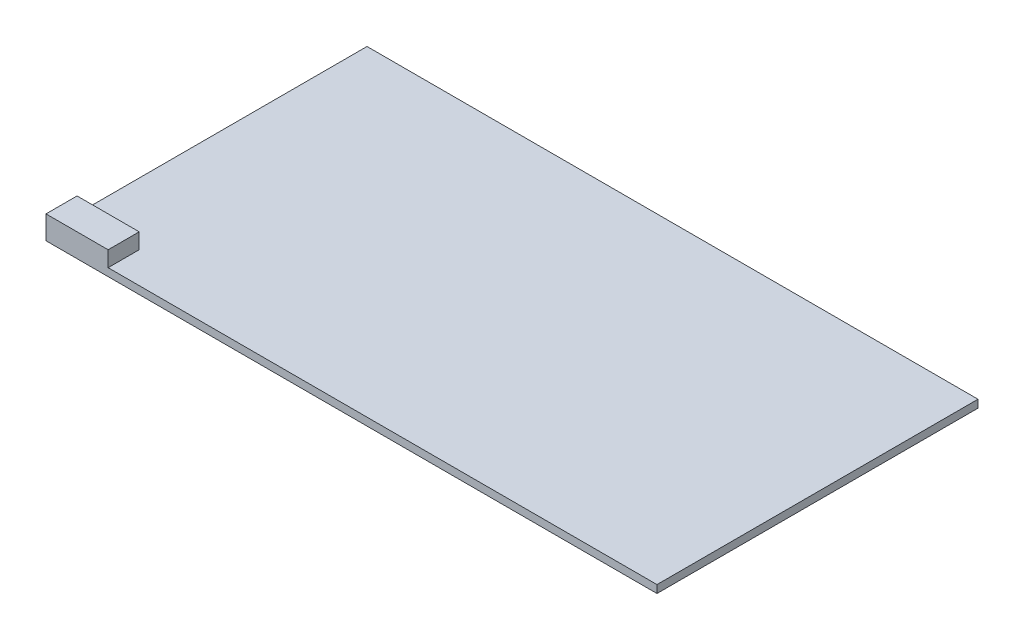
SolidWorks part; units mm, degrees
other "Cámara1"
other "标注1"
sketch "草图2" plane through (66, 3.1, 0) normal (0.0333, 0.9991, 0.0253) x (0.9981, -0.032, -0.0531)
other "标注2"
sketch "草图3" plane through (66, 3.1, 0) normal (0.0333, 0.9991, 0.0253) x (0.9981, -0.032, -0.0531)
ref_plane "Alzado" through (0, 0, 0) normal (0, 0, 1) x (1, 0, 0)
ref_plane "Planta" through (0, 0, 0) normal (0, 1, 0) x (1, 0, 0)
ref_plane "Vista lateral" through (0, 0, 0) normal (1, 0, 0) x (0, 0, -1)
sketch "Croquis1" plane through (0, 0, 0) normal (0, 1, 0) x (1, 0, 0)
  line L1 (0, 0) -> (118, 0)
  line L3 (0, 62) -> (118, 62)
  line L4 (118, 0) -> (118, 62)
  line L7 (52, 31) -> (118, 31) construction
  line L8 (0, 62) -> (0, 0)
  dimension "D2" = 118
  dimension "D1" = 62
extrude "Saliente-Extruir1" add sketch "Croquis1" along normal blind 1.5
sketch "Croquis2" plane through (0, 1.5, 0) normal (0, 1, 0) x (1, 0, 0)
  line L1 (0.8, 5.8) -> (5.8, 5.8)
  line L2 (0.8, 5.8) -> (0.8, 0.8)
  line L3 (0.8, 0.8) -> (5.8, 0.8)
  line L4 (5.8, 5.8) -> (5.8, 0.8)
  line L5 (0, 0) -> (118, 0) construction
  line L6 (9.3, 5.8) -> (14.3, 5.8)
  line L7 (9.3, 5.8) -> (9.3, 0.8)
  line L8 (9.3, 0.8) -> (14.3, 0.8)
  line L9 (14.3, 5.8) -> (14.3, 0.8)
  line L10 (17.8, 5.8) -> (22.8, 5.8)
  line L11 (17.8, 5.8) -> (17.8, 0.8)
  line L12 (17.8, 0.8) -> (22.8, 0.8)
  line L13 (22.8, 5.8) -> (22.8, 0.8)
  line L14 (26.3, 5.8) -> (31.3, 5.8)
  line L15 (26.3, 5.8) -> (26.3, 0.8)
  line L16 (26.3, 0.8) -> (31.3, 0.8)
  line L17 (31.3, 5.8) -> (31.3, 0.8)
  line L18 (34.8, 5.8) -> (39.8, 5.8)
  line L19 (34.8, 5.8) -> (34.8, 0.8)
  line L20 (34.8, 0.8) -> (39.8, 0.8)
  line L21 (39.8, 5.8) -> (39.8, 0.8)
  line L22 (43.3, 5.8) -> (48.3, 5.8)
  line L23 (43.3, 5.8) -> (43.3, 0.8)
  line L24 (43.3, 0.8) -> (48.3, 0.8)
  line L25 (48.3, 5.8) -> (48.3, 0.8)
  line L26 (51.8, 5.8) -> (56.8, 5.8)
  line L27 (51.8, 5.8) -> (51.8, 0.8)
  line L28 (51.8, 0.8) -> (56.8, 0.8)
  line L29 (56.8, 5.8) -> (56.8, 0.8)
  line L30 (60.3, 5.8) -> (65.3, 5.8)
  line L31 (60.3, 5.8) -> (60.3, 0.8)
  line L32 (60.3, 0.8) -> (65.3, 0.8)
  line L33 (65.3, 5.8) -> (65.3, 0.8)
  line L34 (9.3, 14.3) -> (14.3, 14.3)
  line L35 (9.3, 14.3) -> (9.3, 9.3)
  line L36 (9.3, 9.3) -> (14.3, 9.3)
  line L37 (14.3, 14.3) -> (14.3, 9.3)
  line L38 (17.8, 14.3) -> (22.8, 14.3)
  line L39 (17.8, 14.3) -> (17.8, 9.3)
  line L40 (17.8, 9.3) -> (22.8, 9.3)
  line L41 (22.8, 14.3) -> (22.8, 9.3)
  line L42 (26.3, 14.3) -> (31.3, 14.3)
  line L43 (26.3, 14.3) -> (26.3, 9.3)
  line L44 (26.3, 9.3) -> (31.3, 9.3)
  line L45 (31.3, 14.3) -> (31.3, 9.3)
  line L46 (34.8, 14.3) -> (39.8, 14.3)
  line L47 (34.8, 14.3) -> (34.8, 9.3)
  line L48 (34.8, 9.3) -> (39.8, 9.3)
  line L49 (39.8, 14.3) -> (39.8, 9.3)
  line L50 (43.3, 14.3) -> (48.3, 14.3)
  line L51 (43.3, 14.3) -> (43.3, 9.3)
  line L52 (43.3, 9.3) -> (48.3, 9.3)
  line L53 (48.3, 14.3) -> (48.3, 9.3)
  line L54 (51.8, 14.3) -> (56.8, 14.3)
  line L55 (51.8, 14.3) -> (51.8, 9.3)
  line L56 (51.8, 9.3) -> (56.8, 9.3)
  line L57 (56.8, 14.3) -> (56.8, 9.3)
  line L58 (60.3, 14.3) -> (65.3, 14.3)
  line L59 (60.3, 14.3) -> (60.3, 9.3)
  line L60 (60.3, 9.3) -> (65.3, 9.3)
  line L61 (65.3, 14.3) -> (65.3, 9.3)
  line L62 (9.3, 22.8) -> (14.3, 22.8)
  line L63 (9.3, 22.8) -> (9.3, 17.8)
  line L64 (9.3, 17.8) -> (14.3, 17.8)
  line L65 (14.3, 22.8) -> (14.3, 17.8)
  line L66 (17.8, 22.8) -> (22.8, 22.8)
  line L67 (17.8, 22.8) -> (17.8, 17.8)
  line L68 (17.8, 17.8) -> (22.8, 17.8)
  line L69 (22.8, 22.8) -> (22.8, 17.8)
  line L70 (26.3, 22.8) -> (31.3, 22.8)
  line L71 (26.3, 22.8) -> (26.3, 17.8)
  line L72 (26.3, 17.8) -> (31.3, 17.8)
  line L73 (31.3, 22.8) -> (31.3, 17.8)
  line L74 (34.8, 22.8) -> (39.8, 22.8)
  line L75 (34.8, 22.8) -> (34.8, 17.8)
  line L76 (34.8, 17.8) -> (39.8, 17.8)
  line L77 (39.8, 22.8) -> (39.8, 17.8)
  line L78 (43.3, 22.8) -> (48.3, 22.8)
  line L79 (43.3, 22.8) -> (43.3, 17.8)
  line L80 (43.3, 17.8) -> (48.3, 17.8)
  line L81 (48.3, 22.8) -> (48.3, 17.8)
  line L82 (51.8, 22.8) -> (56.8, 22.8)
  line L83 (51.8, 22.8) -> (51.8, 17.8)
  line L84 (51.8, 17.8) -> (56.8, 17.8)
  line L85 (56.8, 22.8) -> (56.8, 17.8)
  line L86 (60.3, 22.8) -> (65.3, 22.8)
  line L87 (60.3, 22.8) -> (60.3, 17.8)
  line L88 (60.3, 17.8) -> (65.3, 17.8)
  line L89 (65.3, 22.8) -> (65.3, 17.8)
  line L90 (9.3, 31.3) -> (14.3, 31.3)
  line L91 (9.3, 31.3) -> (9.3, 26.3)
  line L92 (9.3, 26.3) -> (14.3, 26.3)
  line L93 (14.3, 31.3) -> (14.3, 26.3)
  line L94 (17.8, 31.3) -> (22.8, 31.3)
  line L95 (17.8, 31.3) -> (17.8, 26.3)
  line L96 (17.8, 26.3) -> (22.8, 26.3)
  line L97 (22.8, 31.3) -> (22.8, 26.3)
  line L98 (26.3, 31.3) -> (31.3, 31.3)
  line L99 (26.3, 31.3) -> (26.3, 26.3)
  line L100 (26.3, 26.3) -> (31.3, 26.3)
  line L101 (31.3, 31.3) -> (31.3, 26.3)
  line L102 (34.8, 31.3) -> (39.8, 31.3)
  line L103 (34.8, 31.3) -> (34.8, 26.3)
  line L104 (34.8, 26.3) -> (39.8, 26.3)
  line L105 (39.8, 31.3) -> (39.8, 26.3)
  line L106 (43.3, 31.3) -> (48.3, 31.3)
  line L107 (43.3, 31.3) -> (43.3, 26.3)
  line L108 (43.3, 26.3) -> (48.3, 26.3)
  line L109 (48.3, 31.3) -> (48.3, 26.3)
  line L110 (51.8, 31.3) -> (56.8, 31.3)
  line L111 (51.8, 31.3) -> (51.8, 26.3)
  line L112 (51.8, 26.3) -> (56.8, 26.3)
  line L113 (56.8, 31.3) -> (56.8, 26.3)
  line L114 (60.3, 31.3) -> (65.3, 31.3)
  line L115 (60.3, 31.3) -> (60.3, 26.3)
  line L116 (60.3, 26.3) -> (65.3, 26.3)
  line L117 (65.3, 31.3) -> (65.3, 26.3)
  line L118 (9.3, 39.8) -> (14.3, 39.8)
  line L119 (9.3, 39.8) -> (9.3, 34.8)
  line L120 (9.3, 34.8) -> (14.3, 34.8)
  line L121 (14.3, 39.8) -> (14.3, 34.8)
  line L122 (17.8, 39.8) -> (22.8, 39.8)
  line L123 (17.8, 39.8) -> (17.8, 34.8)
  line L124 (17.8, 34.8) -> (22.8, 34.8)
  line L125 (22.8, 39.8) -> (22.8, 34.8)
  line L126 (26.3, 39.8) -> (31.3, 39.8)
  line L127 (26.3, 39.8) -> (26.3, 34.8)
  line L128 (26.3, 34.8) -> (31.3, 34.8)
  line L129 (31.3, 39.8) -> (31.3, 34.8)
  line L130 (34.8, 39.8) -> (39.8, 39.8)
  line L131 (34.8, 39.8) -> (34.8, 34.8)
  line L132 (34.8, 34.8) -> (39.8, 34.8)
  line L133 (39.8, 39.8) -> (39.8, 34.8)
  line L134 (43.3, 39.8) -> (48.3, 39.8)
  line L135 (43.3, 39.8) -> (43.3, 34.8)
  line L136 (43.3, 34.8) -> (48.3, 34.8)
  line L137 (48.3, 39.8) -> (48.3, 34.8)
  line L138 (51.8, 39.8) -> (56.8, 39.8)
  line L139 (51.8, 39.8) -> (51.8, 34.8)
  line L140 (51.8, 34.8) -> (56.8, 34.8)
  line L141 (56.8, 39.8) -> (56.8, 34.8)
  line L142 (60.3, 39.8) -> (65.3, 39.8)
  line L143 (60.3, 39.8) -> (60.3, 34.8)
  line L144 (60.3, 34.8) -> (65.3, 34.8)
  line L145 (65.3, 39.8) -> (65.3, 34.8)
  line L146 (9.3, 48.3) -> (14.3, 48.3)
  line L147 (9.3, 48.3) -> (9.3, 43.3)
  line L148 (9.3, 43.3) -> (14.3, 43.3)
  line L149 (14.3, 48.3) -> (14.3, 43.3)
  line L150 (17.8, 48.3) -> (22.8, 48.3)
  line L151 (17.8, 48.3) -> (17.8, 43.3)
  line L152 (17.8, 43.3) -> (22.8, 43.3)
  line L153 (22.8, 48.3) -> (22.8, 43.3)
  line L154 (26.3, 48.3) -> (31.3, 48.3)
  line L155 (26.3, 48.3) -> (26.3, 43.3)
  line L156 (26.3, 43.3) -> (31.3, 43.3)
  line L157 (31.3, 48.3) -> (31.3, 43.3)
  line L158 (34.8, 48.3) -> (39.8, 48.3)
  line L159 (34.8, 48.3) -> (34.8, 43.3)
  line L160 (34.8, 43.3) -> (39.8, 43.3)
  line L161 (39.8, 48.3) -> (39.8, 43.3)
  line L162 (43.3, 48.3) -> (48.3, 48.3)
  line L163 (43.3, 48.3) -> (43.3, 43.3)
  line L164 (43.3, 43.3) -> (48.3, 43.3)
  line L165 (48.3, 48.3) -> (48.3, 43.3)
  line L166 (51.8, 48.3) -> (56.8, 48.3)
  line L167 (51.8, 48.3) -> (51.8, 43.3)
  line L168 (51.8, 43.3) -> (56.8, 43.3)
  line L169 (56.8, 48.3) -> (56.8, 43.3)
  line L170 (60.3, 48.3) -> (65.3, 48.3)
  line L171 (60.3, 48.3) -> (60.3, 43.3)
  line L172 (60.3, 43.3) -> (65.3, 43.3)
  line L173 (65.3, 48.3) -> (65.3, 43.3)
  line L174 (9.3, 56.8) -> (14.3, 56.8)
  line L175 (9.3, 56.8) -> (9.3, 51.8)
  line L176 (9.3, 51.8) -> (14.3, 51.8)
  line L177 (14.3, 56.8) -> (14.3, 51.8)
  line L178 (17.8, 56.8) -> (22.8, 56.8)
  line L179 (17.8, 56.8) -> (17.8, 51.8)
  line L180 (17.8, 51.8) -> (22.8, 51.8)
  line L181 (22.8, 56.8) -> (22.8, 51.8)
  line L182 (26.3, 56.8) -> (31.3, 56.8)
  line L183 (26.3, 56.8) -> (26.3, 51.8)
  line L184 (26.3, 51.8) -> (31.3, 51.8)
  line L185 (31.3, 56.8) -> (31.3, 51.8)
  line L186 (34.8, 56.8) -> (39.8, 56.8)
  line L187 (34.8, 56.8) -> (34.8, 51.8)
  line L188 (34.8, 51.8) -> (39.8, 51.8)
  line L189 (39.8, 56.8) -> (39.8, 51.8)
  line L190 (43.3, 56.8) -> (48.3, 56.8)
  line L191 (43.3, 56.8) -> (43.3, 51.8)
  line L192 (43.3, 51.8) -> (48.3, 51.8)
  line L193 (48.3, 56.8) -> (48.3, 51.8)
  line L194 (51.8, 56.8) -> (56.8, 56.8)
  line L195 (51.8, 56.8) -> (51.8, 51.8)
  line L196 (51.8, 51.8) -> (56.8, 51.8)
  line L197 (56.8, 56.8) -> (56.8, 51.8)
  line L198 (60.3, 56.8) -> (65.3, 56.8)
  line L199 (60.3, 56.8) -> (60.3, 51.8)
  line L200 (60.3, 51.8) -> (65.3, 51.8)
  line L201 (65.3, 56.8) -> (65.3, 51.8)
  line L202 (9.3, 65.3) -> (14.3, 65.3)
  line L203 (9.3, 65.3) -> (9.3, 60.3)
  line L204 (9.3, 60.3) -> (14.3, 60.3)
  line L205 (14.3, 65.3) -> (14.3, 60.3)
  line L206 (17.8, 65.3) -> (22.8, 65.3)
  line L207 (17.8, 65.3) -> (17.8, 60.3)
  line L208 (17.8, 60.3) -> (22.8, 60.3)
  line L209 (22.8, 65.3) -> (22.8, 60.3)
  line L210 (26.3, 65.3) -> (31.3, 65.3)
  line L211 (26.3, 65.3) -> (26.3, 60.3)
  line L212 (26.3, 60.3) -> (31.3, 60.3)
  line L213 (31.3, 65.3) -> (31.3, 60.3)
  line L214 (34.8, 65.3) -> (39.8, 65.3)
  line L215 (34.8, 65.3) -> (34.8, 60.3)
  line L216 (34.8, 60.3) -> (39.8, 60.3)
  line L217 (39.8, 65.3) -> (39.8, 60.3)
  line L218 (43.3, 65.3) -> (48.3, 65.3)
  line L219 (43.3, 65.3) -> (43.3, 60.3)
  line L220 (43.3, 60.3) -> (48.3, 60.3)
  line L221 (48.3, 65.3) -> (48.3, 60.3)
  line L222 (51.8, 65.3) -> (56.8, 65.3)
  line L223 (51.8, 65.3) -> (51.8, 60.3)
  line L224 (51.8, 60.3) -> (56.8, 60.3)
  line L225 (56.8, 65.3) -> (56.8, 60.3)
  line L226 (60.3, 65.3) -> (65.3, 65.3)
  line L227 (60.3, 65.3) -> (60.3, 60.3)
  line L228 (60.3, 60.3) -> (65.3, 60.3)
  line L229 (65.3, 65.3) -> (65.3, 60.3)
  line L230 (0.8, 14.3) -> (5.8, 14.3)
  line L231 (0.8, 14.3) -> (0.8, 9.3)
  line L232 (0.8, 9.3) -> (5.8, 9.3)
  line L233 (5.8, 14.3) -> (5.8, 9.3)
  line L234 (0.8, 22.8) -> (5.8, 22.8)
  line L235 (0.8, 22.8) -> (0.8, 17.8)
  line L236 (0.8, 17.8) -> (5.8, 17.8)
  line L237 (5.8, 22.8) -> (5.8, 17.8)
  line L238 (0.8, 31.3) -> (5.8, 31.3)
  line L239 (0.8, 31.3) -> (0.8, 26.3)
  line L240 (0.8, 26.3) -> (5.8, 26.3)
  line L241 (5.8, 31.3) -> (5.8, 26.3)
  line L242 (0.8, 39.8) -> (5.8, 39.8)
  line L243 (0.8, 39.8) -> (0.8, 34.8)
  line L244 (0.8, 34.8) -> (5.8, 34.8)
  line L245 (5.8, 39.8) -> (5.8, 34.8)
  line L246 (0.8, 48.3) -> (5.8, 48.3)
  line L247 (0.8, 48.3) -> (0.8, 43.3)
  line L248 (0.8, 43.3) -> (5.8, 43.3)
  line L249 (5.8, 48.3) -> (5.8, 43.3)
  line L250 (0.8, 56.8) -> (5.8, 56.8)
  line L251 (0.8, 56.8) -> (0.8, 51.8)
  line L252 (0.8, 51.8) -> (5.8, 51.8)
  line L253 (5.8, 56.8) -> (5.8, 51.8)
  line L254 (0.8, 65.3) -> (5.8, 65.3)
  line L255 (0.8, 65.3) -> (0.8, 60.3)
  line L256 (0.8, 60.3) -> (5.8, 60.3)
  line L257 (5.8, 65.3) -> (5.8, 60.3)
  line L258 (0, 62) -> (0, 0) construction
  dimension "D1" = 5
  dimension "D2" = 0.8
  dimension "D3" = 0.8
  dimension "D6" = 8.5
  dimension "D4" = 8
  dimension "D5" = 8
extrude "Saliente-Extruir2" [suppressed] add sketch "Croquis2" along normal blind 1.6 separate body
sketch "Croquis3" [suppressed] plane through (0, 3.1, 0) normal (0, 1, 0) x (1, 0, 0)
  line L1 (3.3, 3.3) -> (3.26, 11.7999) construction
  line L2 (3.3, 5.8) -> (3.3, 0.8) construction
  line L3 (5.8, 5.8) -> (0.8, 5.8) construction
  line L4 (0.8, 0.8) -> (5.8, 0.8) construction
  line L6 (5.8, 0.8) -> (5.8, 5.8) construction
  circle A0 centre (3.3, 3.3) radius 1.75
  circle A1 centre (11.8, 3.3) radius 1.75
  circle A2 centre (20.3, 3.3) radius 1.75
  circle A3 centre (28.8, 3.3) radius 1.75
  circle A4 centre (37.3, 3.3) radius 1.75
  circle A5 centre (45.8, 3.3) radius 1.75
  circle A6 centre (54.3, 3.3) radius 1.75
  circle A7 centre (62.8, 3.3) radius 1.75
  circle A8 centre (11.8, 11.8) radius 1.75
  circle A9 centre (20.3, 11.8) radius 1.75
  circle A10 centre (28.8, 11.8) radius 1.75
  circle A11 centre (37.3, 11.8) radius 1.75
  circle A12 centre (45.8, 11.8) radius 1.75
  circle A13 centre (54.3, 11.8) radius 1.75
  circle A14 centre (62.8, 11.8) radius 1.75
  circle A15 centre (11.8, 20.3) radius 1.75
  circle A16 centre (20.3, 20.3) radius 1.75
  circle A17 centre (28.8, 20.3) radius 1.75
  circle A18 centre (37.3, 20.3) radius 1.75
  circle A19 centre (45.8, 20.3) radius 1.75
  circle A20 centre (54.3, 20.3) radius 1.75
  circle A21 centre (62.8, 20.3) radius 1.75
  circle A22 centre (11.8, 28.8) radius 1.75
  circle A23 centre (20.3, 28.8) radius 1.75
  circle A24 centre (28.8, 28.8) radius 1.75
  circle A25 centre (37.3, 28.8) radius 1.75
  circle A26 centre (45.8, 28.8) radius 1.75
  circle A27 centre (54.3, 28.8) radius 1.75
  circle A28 centre (62.8, 28.8) radius 1.75
  circle A29 centre (11.8, 37.3) radius 1.75
  circle A30 centre (20.3, 37.3) radius 1.75
  circle A31 centre (28.8, 37.3) radius 1.75
  circle A32 centre (37.3, 37.3) radius 1.75
  circle A33 centre (45.8, 37.3) radius 1.75
  circle A34 centre (54.3, 37.3) radius 1.75
  circle A35 centre (62.8, 37.3) radius 1.75
  circle A36 centre (11.8, 45.8) radius 1.75
  circle A37 centre (20.3, 45.8) radius 1.75
  circle A38 centre (28.8, 45.8) radius 1.75
  circle A39 centre (37.3, 45.8) radius 1.75
  circle A40 centre (45.8, 45.8) radius 1.75
  circle A41 centre (54.3, 45.8) radius 1.75
  circle A42 centre (62.8, 45.8) radius 1.75
  circle A43 centre (11.8, 54.3) radius 1.75
  circle A44 centre (20.3, 54.3) radius 1.75
  circle A45 centre (28.8, 54.3) radius 1.75
  circle A46 centre (37.3, 54.3) radius 1.75
  circle A47 centre (45.8, 54.3) radius 1.75
  circle A48 centre (54.3, 54.3) radius 1.75
  circle A49 centre (62.8, 54.3) radius 1.75
  circle A50 centre (11.8, 62.8) radius 1.75
  circle A51 centre (20.3, 62.8) radius 1.75
  circle A52 centre (28.8, 62.8) radius 1.75
  circle A53 centre (37.3, 62.8) radius 1.75
  circle A54 centre (45.8, 62.8) radius 1.75
  circle A55 centre (54.3, 62.8) radius 1.75
  circle A56 centre (62.8, 62.8) radius 1.75
  circle A57 centre (3.3, 11.8) radius 1.75
  circle A58 centre (3.3, 20.3) radius 1.75
  circle A59 centre (3.3, 28.8) radius 1.75
  circle A60 centre (3.3, 37.3) radius 1.75
  circle A61 centre (3.3, 45.8) radius 1.75
  circle A62 centre (3.3, 54.3) radius 1.75
  circle A63 centre (3.3, 62.8) radius 1.75
  dimension "D1" = 3.5
  dimension "D3" = 2.5
  dimension "D2" = 8
extrude "切除-拉伸1" [suppressed] cut sketch "Croquis3" against normal blind 0.05
sketch "草图1" [suppressed] plane through (0, 1.5, 0) normal (0, 1, 0) x (1, 0, 0)
  line L0 (3.3, 7.9443) -> (3.3, 7.1557) construction
  line L1 (1.55, 7.9443) -> (5.05, 7.9443)
  line L2 (1.55, 7.9443) -> (1.55, 7.1557)
  line L3 (1.55, 7.1557) -> (5.05, 7.1557)
  line L4 (5.05, 7.9443) -> (5.05, 7.1557)
  line L5 (0.8, 14.3) -> (0.8, 9.3) construction
  line L6 (1.55, 7.55) -> (5.05, 7.55) construction
  line L7 (0.8, 9.3) -> (5.8, 9.3) construction
  line L8 (10.05, 7.9443) -> (10.05, 7.1557)
  line L9 (10.05, 7.9443) -> (13.55, 7.9443)
  line L10 (13.55, 7.9443) -> (13.55, 7.1557)
  line L11 (10.05, 7.1557) -> (13.55, 7.1557)
  line L12 (18.55, 7.9443) -> (18.55, 7.1557)
  line L13 (18.55, 7.9443) -> (22.05, 7.9443)
  line L14 (22.05, 7.9443) -> (22.05, 7.1557)
  line L15 (18.55, 7.1557) -> (22.05, 7.1557)
  line L16 (27.05, 7.9443) -> (27.05, 7.1557)
  line L17 (27.05, 7.9443) -> (30.55, 7.9443)
  line L18 (30.55, 7.9443) -> (30.55, 7.1557)
  line L19 (27.05, 7.1557) -> (30.55, 7.1557)
  line L20 (35.55, 7.9443) -> (35.55, 7.1557)
  line L21 (35.55, 7.9443) -> (39.05, 7.9443)
  line L22 (39.05, 7.9443) -> (39.05, 7.1557)
  line L23 (35.55, 7.1557) -> (39.05, 7.1557)
  line L24 (44.05, 7.9443) -> (44.05, 7.1557)
  line L25 (44.05, 7.9443) -> (47.55, 7.9443)
  line L26 (47.55, 7.9443) -> (47.55, 7.1557)
  line L27 (44.05, 7.1557) -> (47.55, 7.1557)
  line L28 (52.55, 7.9443) -> (52.55, 7.1557)
  line L29 (52.55, 7.9443) -> (56.05, 7.9443)
  line L30 (56.05, 7.9443) -> (56.05, 7.1557)
  line L31 (52.55, 7.1557) -> (56.05, 7.1557)
  line L32 (61.05, 7.9443) -> (61.05, 7.1557)
  line L33 (61.05, 7.9443) -> (64.55, 7.9443)
  line L34 (64.55, 7.9443) -> (64.55, 7.1557)
  line L35 (61.05, 7.1557) -> (64.55, 7.1557)
  line L36 (10.05, 16.4443) -> (10.05, 15.6557)
  line L37 (10.05, 16.4443) -> (13.55, 16.4443)
  line L38 (13.55, 16.4443) -> (13.55, 15.6557)
  line L39 (10.05, 15.6557) -> (13.55, 15.6557)
  line L40 (18.55, 16.4443) -> (18.55, 15.6557)
  line L41 (18.55, 16.4443) -> (22.05, 16.4443)
  line L42 (22.05, 16.4443) -> (22.05, 15.6557)
  line L43 (18.55, 15.6557) -> (22.05, 15.6557)
  line L44 (27.05, 16.4443) -> (27.05, 15.6557)
  line L45 (27.05, 16.4443) -> (30.55, 16.4443)
  line L46 (30.55, 16.4443) -> (30.55, 15.6557)
  line L47 (27.05, 15.6557) -> (30.55, 15.6557)
  line L48 (35.55, 16.4443) -> (35.55, 15.6557)
  line L49 (35.55, 16.4443) -> (39.05, 16.4443)
  line L50 (39.05, 16.4443) -> (39.05, 15.6557)
  line L51 (35.55, 15.6557) -> (39.05, 15.6557)
  line L52 (44.05, 16.4443) -> (44.05, 15.6557)
  line L53 (44.05, 16.4443) -> (47.55, 16.4443)
  line L54 (47.55, 16.4443) -> (47.55, 15.6557)
  line L55 (44.05, 15.6557) -> (47.55, 15.6557)
  line L56 (52.55, 16.4443) -> (52.55, 15.6557)
  line L57 (52.55, 16.4443) -> (56.05, 16.4443)
  line L58 (56.05, 16.4443) -> (56.05, 15.6557)
  line L59 (52.55, 15.6557) -> (56.05, 15.6557)
  line L60 (61.05, 16.4443) -> (61.05, 15.6557)
  line L61 (61.05, 16.4443) -> (64.55, 16.4443)
  line L62 (64.55, 16.4443) -> (64.55, 15.6557)
  line L63 (61.05, 15.6557) -> (64.55, 15.6557)
  line L64 (10.05, 24.9443) -> (10.05, 24.1557)
  line L65 (10.05, 24.9443) -> (13.55, 24.9443)
  line L66 (13.55, 24.9443) -> (13.55, 24.1557)
  line L67 (10.05, 24.1557) -> (13.55, 24.1557)
  line L68 (18.55, 24.9443) -> (18.55, 24.1557)
  line L69 (18.55, 24.9443) -> (22.05, 24.9443)
  line L70 (22.05, 24.9443) -> (22.05, 24.1557)
  line L71 (18.55, 24.1557) -> (22.05, 24.1557)
  line L72 (27.05, 24.9443) -> (27.05, 24.1557)
  line L73 (27.05, 24.9443) -> (30.55, 24.9443)
  line L74 (30.55, 24.9443) -> (30.55, 24.1557)
  line L75 (27.05, 24.1557) -> (30.55, 24.1557)
  line L76 (35.55, 24.9443) -> (35.55, 24.1557)
  line L77 (35.55, 24.9443) -> (39.05, 24.9443)
  line L78 (39.05, 24.9443) -> (39.05, 24.1557)
  line L79 (35.55, 24.1557) -> (39.05, 24.1557)
  line L80 (44.05, 24.9443) -> (44.05, 24.1557)
  line L81 (44.05, 24.9443) -> (47.55, 24.9443)
  line L82 (47.55, 24.9443) -> (47.55, 24.1557)
  line L83 (44.05, 24.1557) -> (47.55, 24.1557)
  line L84 (52.55, 24.9443) -> (52.55, 24.1557)
  line L85 (52.55, 24.9443) -> (56.05, 24.9443)
  line L86 (56.05, 24.9443) -> (56.05, 24.1557)
  line L87 (52.55, 24.1557) -> (56.05, 24.1557)
  line L88 (61.05, 24.9443) -> (61.05, 24.1557)
  line L89 (61.05, 24.9443) -> (64.55, 24.9443)
  line L90 (64.55, 24.9443) -> (64.55, 24.1557)
  line L91 (61.05, 24.1557) -> (64.55, 24.1557)
  line L92 (10.05, 33.4443) -> (10.05, 32.6557)
  line L93 (10.05, 33.4443) -> (13.55, 33.4443)
  line L94 (13.55, 33.4443) -> (13.55, 32.6557)
  line L95 (10.05, 32.6557) -> (13.55, 32.6557)
  line L96 (18.55, 33.4443) -> (18.55, 32.6557)
  line L97 (18.55, 33.4443) -> (22.05, 33.4443)
  line L98 (22.05, 33.4443) -> (22.05, 32.6557)
  line L99 (18.55, 32.6557) -> (22.05, 32.6557)
  line L100 (27.05, 33.4443) -> (27.05, 32.6557)
  line L101 (27.05, 33.4443) -> (30.55, 33.4443)
  line L102 (30.55, 33.4443) -> (30.55, 32.6557)
  line L103 (27.05, 32.6557) -> (30.55, 32.6557)
  line L104 (35.55, 33.4443) -> (35.55, 32.6557)
  line L105 (35.55, 33.4443) -> (39.05, 33.4443)
  line L106 (39.05, 33.4443) -> (39.05, 32.6557)
  line L107 (35.55, 32.6557) -> (39.05, 32.6557)
  line L108 (44.05, 33.4443) -> (44.05, 32.6557)
  line L109 (44.05, 33.4443) -> (47.55, 33.4443)
  line L110 (47.55, 33.4443) -> (47.55, 32.6557)
  line L111 (44.05, 32.6557) -> (47.55, 32.6557)
  line L112 (52.55, 33.4443) -> (52.55, 32.6557)
  line L113 (52.55, 33.4443) -> (56.05, 33.4443)
  line L114 (56.05, 33.4443) -> (56.05, 32.6557)
  line L115 (52.55, 32.6557) -> (56.05, 32.6557)
  line L116 (61.05, 33.4443) -> (61.05, 32.6557)
  line L117 (61.05, 33.4443) -> (64.55, 33.4443)
  line L118 (64.55, 33.4443) -> (64.55, 32.6557)
  line L119 (61.05, 32.6557) -> (64.55, 32.6557)
  line L120 (10.05, 41.9443) -> (10.05, 41.1557)
  line L121 (10.05, 41.9443) -> (13.55, 41.9443)
  line L122 (13.55, 41.9443) -> (13.55, 41.1557)
  line L123 (10.05, 41.1557) -> (13.55, 41.1557)
  line L124 (18.55, 41.9443) -> (18.55, 41.1557)
  line L125 (18.55, 41.9443) -> (22.05, 41.9443)
  line L126 (22.05, 41.9443) -> (22.05, 41.1557)
  line L127 (18.55, 41.1557) -> (22.05, 41.1557)
  line L128 (27.05, 41.9443) -> (27.05, 41.1557)
  line L129 (27.05, 41.9443) -> (30.55, 41.9443)
  line L130 (30.55, 41.9443) -> (30.55, 41.1557)
  line L131 (27.05, 41.1557) -> (30.55, 41.1557)
  line L132 (35.55, 41.9443) -> (35.55, 41.1557)
  line L133 (35.55, 41.9443) -> (39.05, 41.9443)
  line L134 (39.05, 41.9443) -> (39.05, 41.1557)
  line L135 (35.55, 41.1557) -> (39.05, 41.1557)
  line L136 (44.05, 41.9443) -> (44.05, 41.1557)
  line L137 (44.05, 41.9443) -> (47.55, 41.9443)
  line L138 (47.55, 41.9443) -> (47.55, 41.1557)
  line L139 (44.05, 41.1557) -> (47.55, 41.1557)
  line L140 (52.55, 41.9443) -> (52.55, 41.1557)
  line L141 (52.55, 41.9443) -> (56.05, 41.9443)
  line L142 (56.05, 41.9443) -> (56.05, 41.1557)
  line L143 (52.55, 41.1557) -> (56.05, 41.1557)
  line L144 (61.05, 41.9443) -> (61.05, 41.1557)
  line L145 (61.05, 41.9443) -> (64.55, 41.9443)
  line L146 (64.55, 41.9443) -> (64.55, 41.1557)
  line L147 (61.05, 41.1557) -> (64.55, 41.1557)
  line L148 (10.05, 50.4443) -> (10.05, 49.6557)
  line L149 (10.05, 50.4443) -> (13.55, 50.4443)
  line L150 (13.55, 50.4443) -> (13.55, 49.6557)
  line L151 (10.05, 49.6557) -> (13.55, 49.6557)
  line L152 (18.55, 50.4443) -> (18.55, 49.6557)
  line L153 (18.55, 50.4443) -> (22.05, 50.4443)
  line L154 (22.05, 50.4443) -> (22.05, 49.6557)
  line L155 (18.55, 49.6557) -> (22.05, 49.6557)
  line L156 (27.05, 50.4443) -> (27.05, 49.6557)
  line L157 (27.05, 50.4443) -> (30.55, 50.4443)
  line L158 (30.55, 50.4443) -> (30.55, 49.6557)
  line L159 (27.05, 49.6557) -> (30.55, 49.6557)
  line L160 (35.55, 50.4443) -> (35.55, 49.6557)
  line L161 (35.55, 50.4443) -> (39.05, 50.4443)
  line L162 (39.05, 50.4443) -> (39.05, 49.6557)
  line L163 (35.55, 49.6557) -> (39.05, 49.6557)
  line L164 (44.05, 50.4443) -> (44.05, 49.6557)
  line L165 (44.05, 50.4443) -> (47.55, 50.4443)
  line L166 (47.55, 50.4443) -> (47.55, 49.6557)
  line L167 (44.05, 49.6557) -> (47.55, 49.6557)
  line L168 (52.55, 50.4443) -> (52.55, 49.6557)
  line L169 (52.55, 50.4443) -> (56.05, 50.4443)
  line L170 (56.05, 50.4443) -> (56.05, 49.6557)
  line L171 (52.55, 49.6557) -> (56.05, 49.6557)
  line L172 (61.05, 50.4443) -> (61.05, 49.6557)
  line L173 (61.05, 50.4443) -> (64.55, 50.4443)
  line L174 (64.55, 50.4443) -> (64.55, 49.6557)
  line L175 (61.05, 49.6557) -> (64.55, 49.6557)
  line L176 (10.05, 58.9443) -> (10.05, 58.1557)
  line L177 (10.05, 58.9443) -> (13.55, 58.9443)
  line L178 (13.55, 58.9443) -> (13.55, 58.1557)
  line L179 (10.05, 58.1557) -> (13.55, 58.1557)
  line L180 (18.55, 58.9443) -> (18.55, 58.1557)
  line L181 (18.55, 58.9443) -> (22.05, 58.9443)
  line L182 (22.05, 58.9443) -> (22.05, 58.1557)
  line L183 (18.55, 58.1557) -> (22.05, 58.1557)
  line L184 (27.05, 58.9443) -> (27.05, 58.1557)
  line L185 (27.05, 58.9443) -> (30.55, 58.9443)
  line L186 (30.55, 58.9443) -> (30.55, 58.1557)
  line L187 (27.05, 58.1557) -> (30.55, 58.1557)
  line L188 (35.55, 58.9443) -> (35.55, 58.1557)
  line L189 (35.55, 58.9443) -> (39.05, 58.9443)
  line L190 (39.05, 58.9443) -> (39.05, 58.1557)
  line L191 (35.55, 58.1557) -> (39.05, 58.1557)
  line L192 (44.05, 58.9443) -> (44.05, 58.1557)
  line L193 (44.05, 58.9443) -> (47.55, 58.9443)
  line L194 (47.55, 58.9443) -> (47.55, 58.1557)
  line L195 (44.05, 58.1557) -> (47.55, 58.1557)
  line L196 (52.55, 58.9443) -> (52.55, 58.1557)
  line L197 (52.55, 58.9443) -> (56.05, 58.9443)
  line L198 (56.05, 58.9443) -> (56.05, 58.1557)
  line L199 (52.55, 58.1557) -> (56.05, 58.1557)
  line L200 (61.05, 58.9443) -> (61.05, 58.1557)
  line L201 (61.05, 58.9443) -> (64.55, 58.9443)
  line L202 (64.55, 58.9443) -> (64.55, 58.1557)
  line L203 (61.05, 58.1557) -> (64.55, 58.1557)
  line L204 (1.55, 16.4443) -> (1.55, 15.6557)
  line L205 (1.55, 16.4443) -> (5.05, 16.4443)
  line L206 (5.05, 16.4443) -> (5.05, 15.6557)
  line L207 (1.55, 15.6557) -> (5.05, 15.6557)
  line L208 (1.55, 24.9443) -> (1.55, 24.1557)
  line L209 (1.55, 24.9443) -> (5.05, 24.9443)
  line L210 (5.05, 24.9443) -> (5.05, 24.1557)
  line L211 (1.55, 24.1557) -> (5.05, 24.1557)
  line L212 (1.55, 33.4443) -> (1.55, 32.6557)
  line L213 (1.55, 33.4443) -> (5.05, 33.4443)
  line L214 (5.05, 33.4443) -> (5.05, 32.6557)
  line L215 (1.55, 32.6557) -> (5.05, 32.6557)
  line L216 (1.55, 41.9443) -> (1.55, 41.1557)
  line L217 (1.55, 41.9443) -> (5.05, 41.9443)
  line L218 (5.05, 41.9443) -> (5.05, 41.1557)
  line L219 (1.55, 41.1557) -> (5.05, 41.1557)
  line L220 (1.55, 50.4443) -> (1.55, 49.6557)
  line L221 (1.55, 50.4443) -> (5.05, 50.4443)
  line L222 (5.05, 50.4443) -> (5.05, 49.6557)
  line L223 (1.55, 49.6557) -> (5.05, 49.6557)
  line L224 (1.55, 58.9443) -> (1.55, 58.1557)
  line L225 (1.55, 58.9443) -> (5.05, 58.9443)
  line L226 (5.05, 58.9443) -> (5.05, 58.1557)
  line L227 (1.55, 58.1557) -> (5.05, 58.1557)
  dimension "D1" = 3.5
  dimension "D2" = 2.5
  dimension "D3" = 1.75
  dimension "D4" = 8
extrude "凸台-拉伸1" [suppressed] add sketch "草图1" along normal blind 0.5
fillet "圆角3" [suppressed] radius 0.2
sketch "草图4" plane through (0, 1.5, 0) normal (0, 1, 0) x (1, 0, 0)
  line L0 (0, 62) -> (0, 0) construction
  line L1 (0, 6) -> (12, 6)
  line L2 (0, 6) -> (0, 0)
  line L3 (0, 0) -> (12, 0)
  line L4 (12, 6) -> (12, 0)
  line L5 (0, 0) -> (118, 0) construction
  dimension "D1" = 12
  dimension "D2" = 6
extrude "凸台-拉伸2" add sketch "草图4" along normal blind 3
